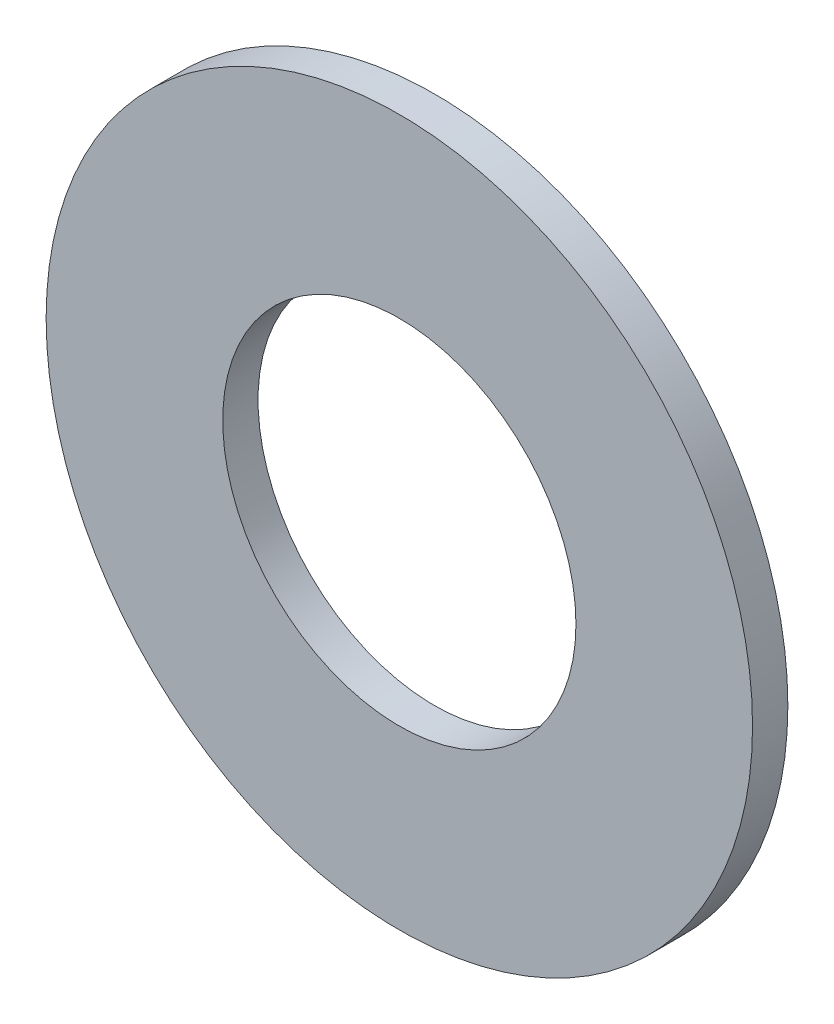
SolidWorks part; units mm, degrees
ref_plane "前视基准面" through (0, 0, 0) normal (0, 0, 1) x (1, 0, 0)
ref_plane "上视基准面" through (0, 0, 0) normal (0, 1, 0) x (1, 0, 0)
ref_plane "右视基准面" through (0, 0, 0) normal (1, 0, 0) x (0, 0, -1)
sketch "草图1" plane through (0, 0, 0) normal (0, 0, 1) x (1, 0, 0)
  circle A0 centre (0, 0) radius 10
  circle A1 centre (0, 0) radius 5
  dimension "D1" = 20
  dimension "D2" = 10
extrude "凸台-拉伸1" add sketch "草图1" along normal blind 1
